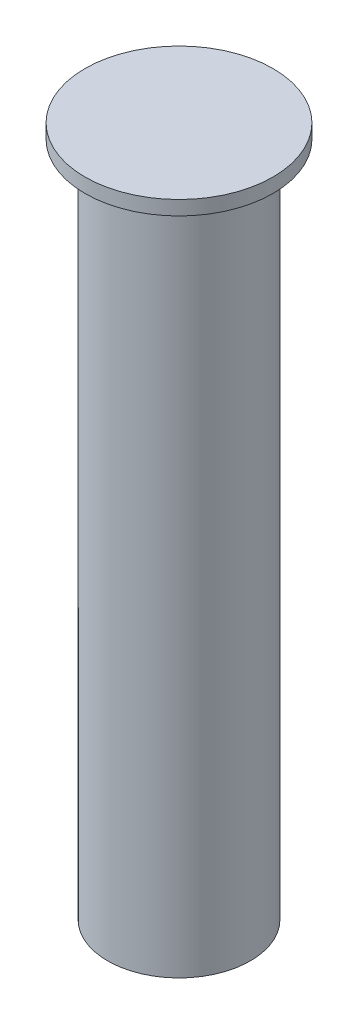
SolidWorks part; units mm, degrees
ref_plane "Płaszczyzna przednia" through (0, 0, 0) normal (0, 0, 1) x (1, 0, 0)
ref_plane "Płaszczyzna górna" through (0, 0, 0) normal (0, 1, 0) x (1, 0, 0)
ref_plane "Płaszczyzna prawa" through (0, 0, 0) normal (1, 0, 0) x (0, 0, -1)
sketch "Szkic1" plane through (0, 0, 0) normal (0, 0, 1) x (1, 0, 0)
  line L0 (0, 0) -> (0, -145) construction
  line L1 (0, 0) -> (-19.75, 0)
  line L2 (-19.75, 0) -> (-19.75, -3)
  line L3 (-19.75, -3) -> (-15, -3)
  line L4 (-15, -3) -> (-15, -145)
  line L5 (-15, -145) -> (0, -145)
  line L6 (0, 0) -> (0, -145)
  dimension "D1" = 39.5
  dimension "D2" = 3
  dimension "D3" = 145
  dimension "D4" = 30
revolve "Obrót1" add sketch "Szkic1" angle 360 about L0
